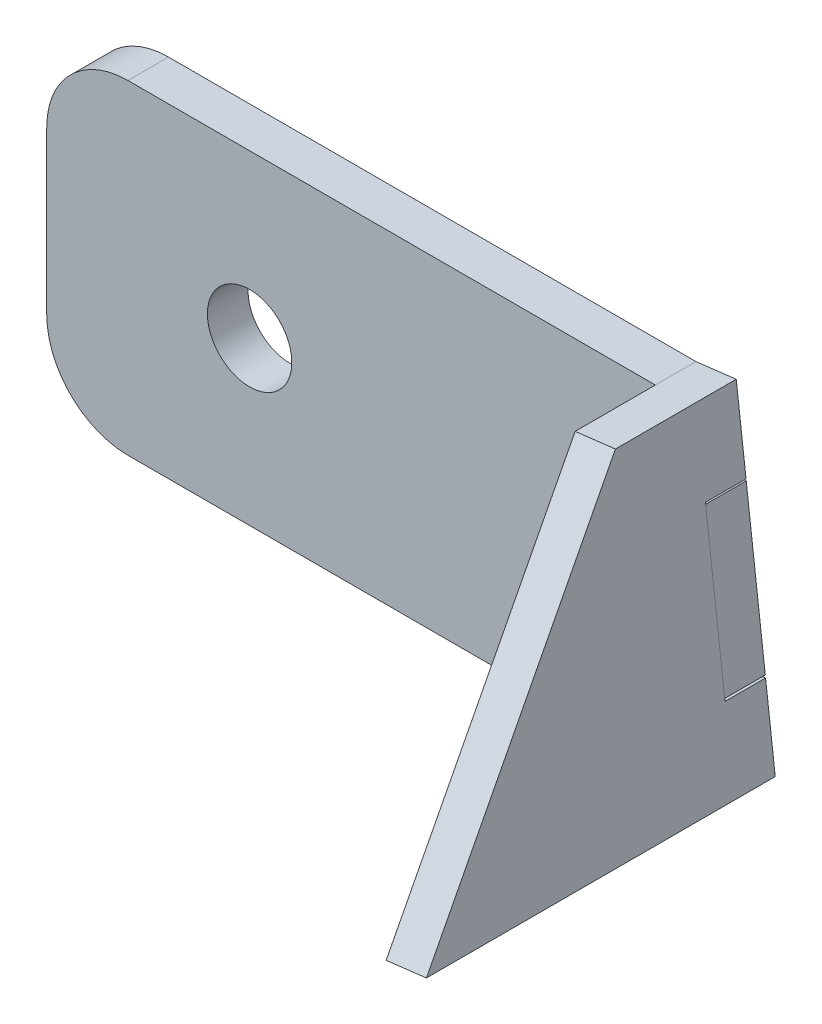
SolidWorks part; units mm, degrees
material "AISI 4130 Steel, annealed at 865C"
ref_plane "Front Plane" through (0, 0, 0) normal (0, 0, 1) x (1, 0, 0)
ref_plane "Top Plane" through (0, 0, 0) normal (0, 1, 0) x (1, 0, 0)
ref_plane "Right Plane" through (0, 0, 0) normal (1, 0, 0) x (0, 0, -1)
sketch "Sketch1" plane through (0, 0, 0) normal (0, 0, 1) x (1, 0, 0)
  line L0 (0, 12.7) -> (-3.0512, -12.7)
  line L1 (0, 12.7) -> (47.625, 12.7)
  line L2 (0, 12.7) -> (0, -12.7) construction
  line L3 (0, -12.7) -> (47.625, -12.7)
  line L4 (47.625, 12.7) -> (47.625, -12.7)
  line L5 (23.8125, -12.7) -> (23.8125, 12.7) construction
  line L6 (0, 0) -> (47.625, 0) construction
  line L7 (-3.0512, -12.7) -> (0, -12.7)
  line L8 (-2.2863, -6.3323) -> (-5.4386, -5.9536)
  line L9 (-5.4386, -5.9536) -> (-3.9173, 6.711)
  line L10 (-3.9173, 6.711) -> (-0.7649, 6.3323)
  line L11 (-0.7801, 6.2062) -> (-3.9324, 6.5849)
  line L12 (-2.2712, -6.2062) -> (-5.4235, -5.8275)
  point P168 (23.8125, 0)
  dimension "D1" = 25.4
  dimension "D2" = 47.625
  dimension "D3" = 83.15
  dimension "D4" = 6.4135
  dimension "D5" = 6.4135
  dimension "D6" = 3.175
  dimension "D7" = 0.127
  dimension "D8" = 0.127
extrude "Boss-Extrude1" add sketch "Sketch1" along normal blind 3.175 contours L0 L7 L3 L4 L1 | L12 L0 L11 L9
sketch "Sketch3" plane through (0, 0, 3.175) normal (0, 0, 1) x (1, 0, 0)
  line L0 (0, 0) -> (31.75, 0) construction
  circle A0 centre (31.75, 0) radius 3.302
  dimension "D1" = 6.604
  dimension "D2" = 31.75
extrude "Cut-Extrude1" cut sketch "Sketch3" against normal through all both and the other way through all contours A0
sketch "Sketch2" plane through (-1.5039, 0.1807, 0) normal (-0.9929, 0.1193, 0) x (0, 0, 1)
  line L0 (0, 6.1958) -> (3.175, 6.1958)
  line L5 (0, 12.6093) -> (0, -12.9733)
  line L6 (0, -12.9733) -> (27.2953, -12.9733)
  line L9 (0, 12.6093) -> (9.4538, 12.6093)
  line L10 (9.4538, 12.6093) -> (27.2953, -12.9733)
  line L11 (3.175, 6.1958) -> (3.175, -6.6233)
  line L13 (3.175, -6.6233) -> (0, -6.6233)
  dimension "D1" = 6.4135
  dimension "D2" = 6.35
  dimension "D3" = 3.175
  dimension "D4" = 27.2953
  dimension "D5" = 31.1896
extrude "Boss-Extrude2" add sketch "Sketch2" along normal blind 3.175 separate body
fillet "Fillet1" radius 6.35 2 edges at (47.625, -12.7, 1.5875) (47.625, 12.7, 1.5875)
mirror "Mirror2" about plane through (0, 0, 0) normal (1, 0, 0) of bodies 102 103
delete or keep bodies "Body-Delete/Keep 1" type delete bodies bodies 102 103
